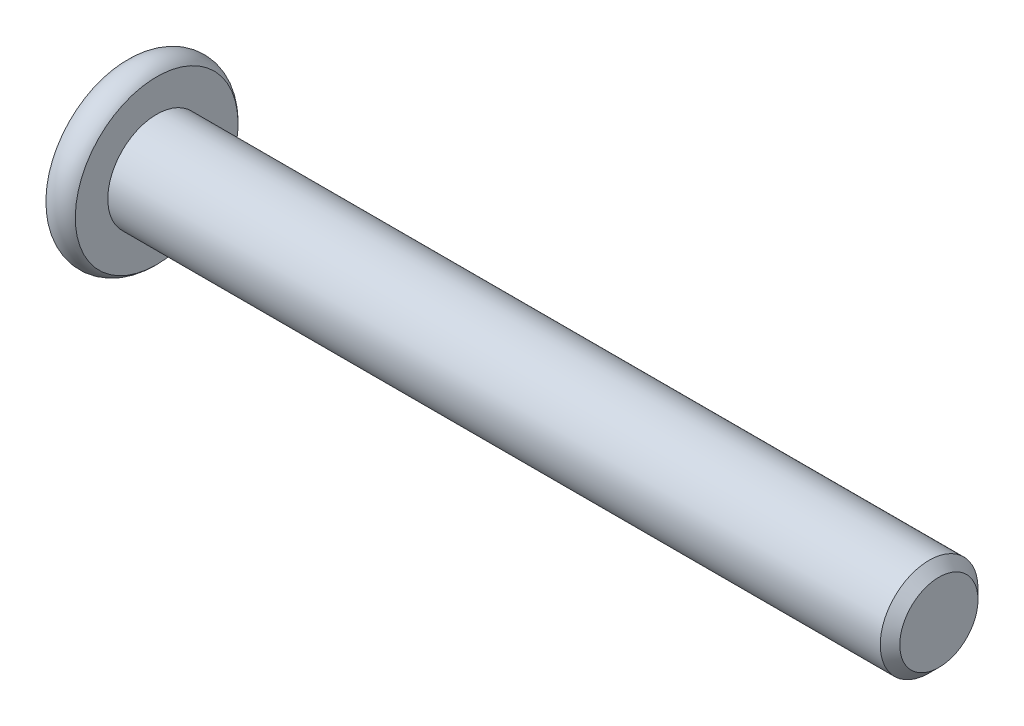
SolidWorks part; units mm, degrees
material "Plain Carbon Steel"
ref_plane "Front Plane" through (0, 0, 0) normal (0, 0, 1) x (1, 0, 0)
ref_plane "Top Plane" through (0, 0, 0) normal (0, 1, 0) x (1, 0, 0)
ref_plane "Right Plane" through (0, 0, 0) normal (1, 0, 0) x (0, 0, -1)
other "M5 x 15"
sketch "Sketch2" plane through (0, 0, 0) normal (1, 0, 0) x (0, 0, -1)
  circle A0 centre (0, 0) radius 2.5
  dimension "D1" = 5
extrude "Boss-Extrude1" add sketch "Sketch2" against normal blind 40
chamfer "Chamfer1" distance 0.5 angle 45 1 edges at (0, 0, -2.5)
sketch "Sketch6" plane through (0, 0, 0) normal (0, 0, 1) x (1, 0, 0)
  line L0 (-41.5, 0) -> (-41.5, 4.1614)
  line L1 (-41.5, 0) -> (-40, 0)
  line L2 (-40.75, 0) -> (-40.75, 3.5) construction
  line L6 (-40, 4.1614) -> (-40, 0)
  line L8 (-40, 0) -> (-14.6471, 0) construction
  line L10 (-40, 2.5) -> (-40, -2.5) construction
  arc A0 (-41.5, 4.1614) -> (-40, 4.1614) centre (-40.75, 3.5) cw
  dimension "D3" = 1
  dimension "D1" = 1.5
  dimension "D2" = 9
revolve "Revolve1" add sketch "Sketch6" angle 360 about L8
sketch "Sketch7" plane through (-41.5, 0, 0) normal (-1, 0, 0) x (0, 0, 1)
  line L1 (0, 1.7321) -> (-1.5, 0.866)
  line L2 (-1.5, 0.866) -> (-1.5, -0.866)
  line L3 (-1.5, -0.866) -> (0, -1.7321)
  line L4 (0, -1.7321) -> (1.5, -0.866)
  line L5 (1.5, -0.866) -> (1.5, 0.866)
  line L6 (1.5, 0.866) -> (0, 1.7321)
  circle A0 centre (0, 0) radius 1.5 construction
  dimension "D1" = 3
extrude "Cut-Extrude1" cut sketch "Sketch7" against normal blind 2.3
sketch "Sketch8" plane through (-41.5, 0, 0) normal (-1, 0, 0) x (0, 0, 1)
  circle A0 centre (0, 0) radius 1.7821
  dimension "D1" = 0.05
extrude "Cut-Extrude2" cut sketch "Sketch8" against normal blind 1 draft 45
